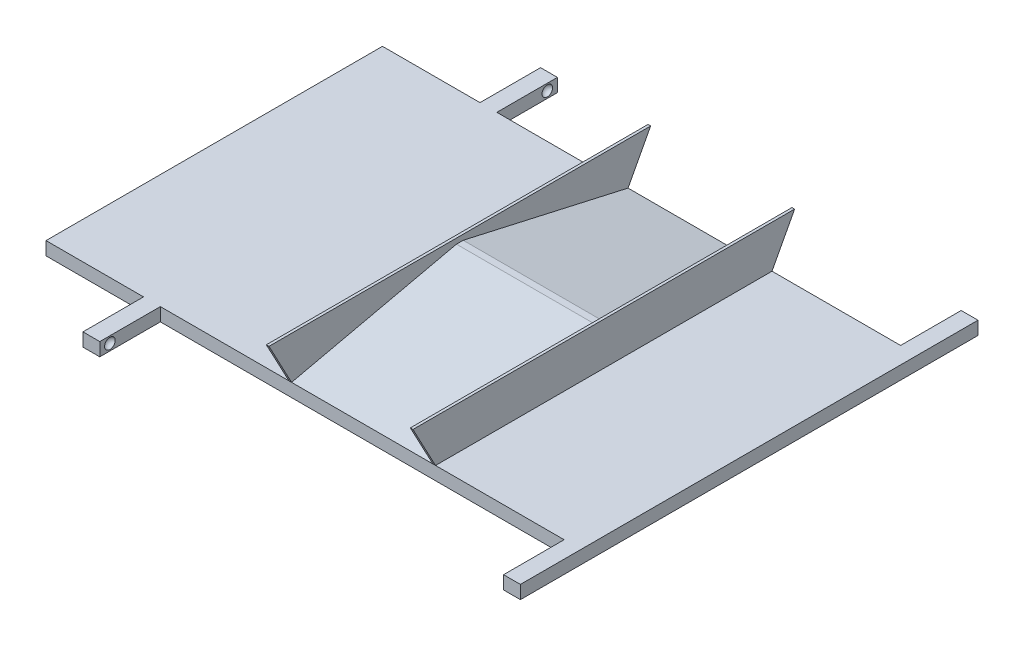
SolidWorks part; units mm, degrees
ref_plane "Front Plane" through (0, 0, 0) normal (0, 0, 1) x (1, 0, 0)
ref_plane "Top Plane" through (0, 0, 0) normal (0, 1, 0) x (1, 0, 0)
ref_plane "Right Plane" through (0, 0, 0) normal (1, 0, 0) x (0, 0, -1)
sketch "Sketch1" plane through (0, 0, 0) normal (0, 1, 0) x (1, 0, 0)
  line L0 (-82.55, -63.5) -> (-82.55, -86.36)
  line L2 (-119.36, 63.5) -> (-119.36, -63.5)
  line L3 (-119.36, -63.5) -> (-82.55, -63.5)
  line L4 (82.55, 86.36) -> (82.55, -86.36)
  line L5 (-82.55, -86.36) -> (-76.2, -86.36)
  line L6 (-76.2, -86.36) -> (-76.2, -63.5)
  line L7 (76.2, -63.5) -> (76.2, -86.36)
  line L8 (76.2, -86.36) -> (82.55, -86.36)
  line L9 (-150.9316, 0) -> (154.55, 0) construction
  line L10 (-76.2, -63.5) -> (76.2, -63.5)
  line L11 (-119.36, 63.5) -> (-82.55, 63.5)
  line L12 (-76.2, 63.5) -> (76.2, 63.5)
  line L13 (76.2, 86.36) -> (82.55, 86.36)
  line L14 (76.2, 63.5) -> (76.2, 86.36)
  line L15 (-76.2, 86.36) -> (-76.2, 63.5)
  line L16 (-82.55, 86.36) -> (-76.2, 86.36)
  line L17 (-82.55, 63.5) -> (-82.55, 86.36)
  point P3 (0, 63.5)
  point P4 (-119.36, 0)
  dimension "D2" = 127
  dimension "D3" = 152.4
  dimension "D4" = 6.35
  dimension "D5" = 22.86
extrude "Boss-Extrude1" add sketch "Sketch1" along normal blind 5
sketch "Sketch4" plane through (-76.2, 0, 0) normal (1, 0, 0) x (0, 0, -1)
  line L0 (-82.55, 4.5) -> (-82.55, 0.5)
  line L1 (-86.36, 5) -> (-86.36, 0) construction
  line L3 (-63.5, 5) -> (-63.5, 0) construction
  arc A0 (-82.55, 0.5) -> (-82.55, 4.5) centre (-82.55, 2.5) ccw
  point P7 (-63.5, 2.5)
  dimension "D1" = 3.81
  dimension "D2" = 2
revolve "Cut-Revolve3" cut sketch "Sketch4" angle 360 about L0
sketch "Sketch5" plane through (76.2, 0, 0) normal (-1, 0, 0) x (0, 0, 1)
  line L1 (82.55, 0.5) -> (82.55, 4.5)
  arc A0 (82.55, 0.5) -> (82.55, 4.5) centre (82.55, 2.5) ccw
  circle A1 centre (82.55, 2.5) radius 2 construction
revolve "Cut-Revolve4" cut sketch "Sketch5" angle 360 about L1
ref_plane "Plane1" through (0, 19.05, 0) normal (0, 1, 0) x (1, 0, 0)
sketch "Sketch6" plane through (0, 19.05, 0) normal (0, 1, 0) x (1, 0, 0)
  line L0 (-135.8762, 0) -> (169.8208, 0) construction
  line L1 (26.67, 1.27) -> (-26.67, 1.27)
  line L2 (26.67, 1.27) -> (26.67, -1.27)
  line L3 (26.67, -1.27) -> (-26.67, -1.27)
  line L4 (-26.67, 1.27) -> (-26.67, -1.27)
  line L5 (0, 126.1175) -> (0, -109.7618) construction
  line L6 (-76.2, -63.5) -> (76.2, -63.5) construction
  point P11 (-26.67, 0)
  point P12 (0, -63.5)
  point P13 (0, -1.27)
  dimension "D1" = 2.54
  dimension "D2" = 53.34
sketch "Sketch7" plane through (0, 5, 0) normal (0, 1, 0) x (1, 0, 0)
  line L0 (0, 108.6619) -> (0, -131.0495) construction
  line L1 (-26.67, -63.5) -> (26.67, -63.5)
  line L2 (-26.67, -63.5) -> (-26.67, 63.5)
  line L3 (-26.67, 63.5) -> (26.67, 63.5)
  line L4 (26.67, -63.5) -> (26.67, 63.5)
  line L6 (-76.2, -63.5) -> (76.2, -63.5) construction
  line L7 (76.2, 63.5) -> (-76.2, 63.5) construction
  point P6 (0, -63.5)
  point P9 (0, -63.5)
  dimension "D1" = 53.34
loft "Loft1" add profiles "Sketch7", "Sketch6"
sketch "Sketch8" plane through (-76.2, 0, 0) normal (1, 0, 0) x (0, 0, -1)
  line L0 (82.55, 4.5) -> (82.55, 0.5)
  line L2 (86.36, 5) -> (86.36, 0) construction
  arc A0 (82.55, 0.5) -> (82.55, 4.5) centre (82.55, 2.5) ccw
  point P5 (86.36, 2.5)
  dimension "D1" = 2
  dimension "D2" = 3.81
revolve "Cut-Revolve5" cut sketch "Sketch8" angle 360 about L0
sketch "Sketch9" plane through (76.2, 0, 0) normal (-1, 0, 0) x (0, 0, 1)
  line L0 (-82.55, 4.405) -> (-82.55, 0.595)
  line L1 (-86.36, 5) -> (-86.36, 0) construction
  arc A0 (-82.55, 0.595) -> (-82.55, 4.405) centre (-82.55, 2.5) ccw
  circle A1 centre (-82.55, 2.5) radius 2 construction
  point P5 (-86.36, 2.5)
  dimension "D1" = 1.905
revolve "Cut-Revolve6" cut sketch "Sketch9" angle 360 about L0
sketch "Sketch10" plane through (26.67, 0, 0) normal (1, 0, 0) x (0, 0, -1)
  line L0 (-1.27, 19.05) -> (1.27, 19.05) construction
  line L1 (-63.5, 5) -> (63.5, 5)
  line L3 (-72.0339, 21.05) -> (72.0339, 21.05)
  line L4 (-63.5, 5) -> (-72.0339, 21.05)
  line L5 (63.5, 5) -> (72.0339, 21.05)
  dimension "D1" = 2
  dimension "D2" = 118
  dimension "D3" = 118
extrude "Boss-Extrude2" add sketch "Sketch10" along normal blind 1
sketch "Sketch11" plane through (-26.67, 0, 0) normal (-1, 0, 0) x (0, 0, 1)
  line L0 (-72.0339, 21.05) -> (72.0339, 21.05) construction
  line L1 (-63.5, 5) -> (63.5, 5)
  line L2 (-63.5, 5) -> (-72.0339, 21.05)
  line L3 (-72.0339, 21.05) -> (72.0339, 21.05)
  line L4 (63.5, 5) -> (72.0339, 21.05)
  line L5 (72.0339, 21.05) -> (63.5, 5) construction
  line L6 (-63.5, 5) -> (-72.0339, 21.05) construction
extrude "Boss-Extrude3" add sketch "Sketch11" along normal blind 1
